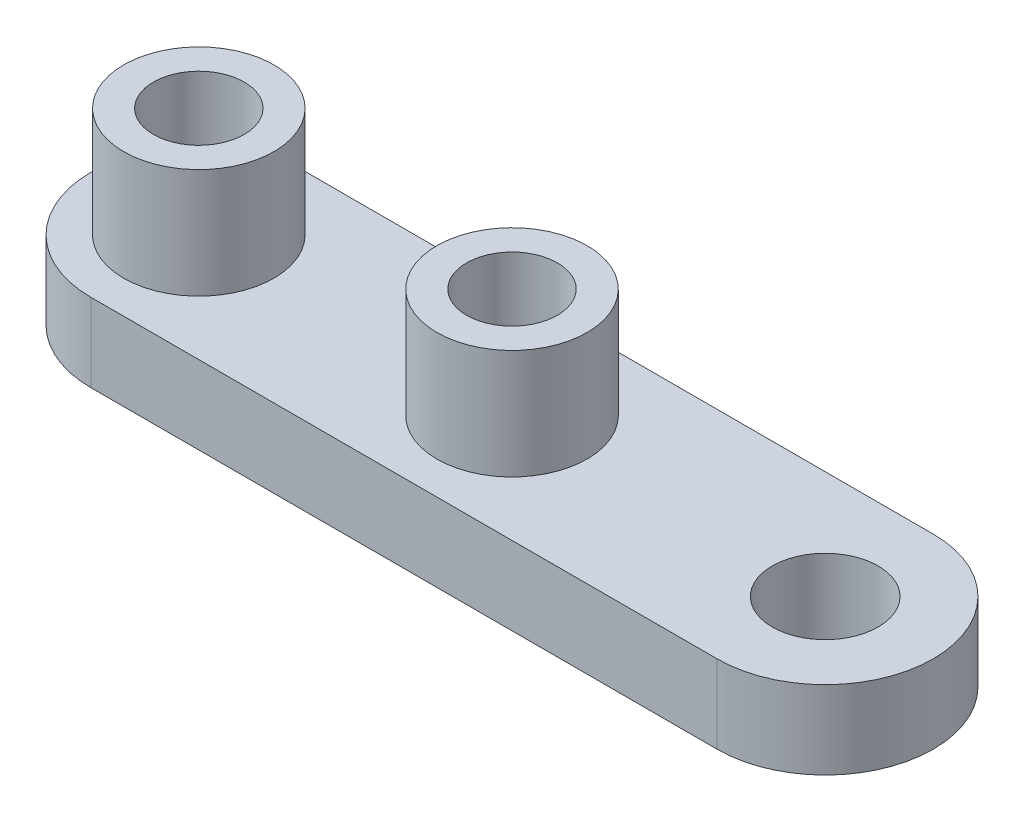
SolidWorks part; units mm, degrees
ref_plane "Alzado" through (0, 0, 0) normal (0, 0, 1) x (1, 0, 0)
ref_plane "Planta" through (0, 0, 0) normal (0, 1, 0) x (1, 0, 0)
ref_plane "Vista lateral" through (0, 0, 0) normal (1, 0, 0) x (0, 0, -1)
sketch "Croquis2" plane through (0, 0, 0) normal (0, 1, 0) x (1, 0, 0)
  line L0 (0, 3.45) -> (20, 3.45)
  line L1 (0, -3.45) -> (20, -3.45)
  circle A0 centre (0, 0) radius 1.45
  circle A1 centre (10, 0) radius 1.45
  circle A2 centre (20, 0) radius 1.45 construction
  arc A3 (20, -3.45) -> (20, 3.45) centre (20, 0) ccw
  arc A4 (0, 3.45) -> (0, -3.45) centre (0, 0) ccw
  circle A6 centre (0, 0) radius 3.45 construction
  circle A7 centre (20, 0) radius 3.45 construction
  point P10 (23.45, 0)
  point P15 (3.45, 0)
  dimension "D1" = 2.9
  dimension "D3" = 2
  dimension "D2" = 3
extrude "Saliente-Extruir1" add sketch "Croquis2" along normal blind 2.5
sketch "Croquis3" plane through (0, 2.5, 0) normal (0, 1, 0) x (1, 0, 0)
  circle A0 centre (0, 0) radius 1.45
  circle A1 centre (10, 0) radius 1.45
  circle A2 centre (0, 0) radius 2.4
  circle A3 centre (10, 0) radius 2.4
  dimension "D1" = 4.8
  dimension "D2" = 4.8
extrude "Saliente-Extruir2" add sketch "Croquis3" along normal blind 3.5
sketch "Croquis4" plane through (0, 2.5, 0) normal (0, 1, 0) x (1, 0, 0)
  circle A0 centre (20, 0) radius 1.69
  dimension "D1" = 3.38
extrude "Cortar-Extruir1" cut sketch "Croquis4" against normal through all
